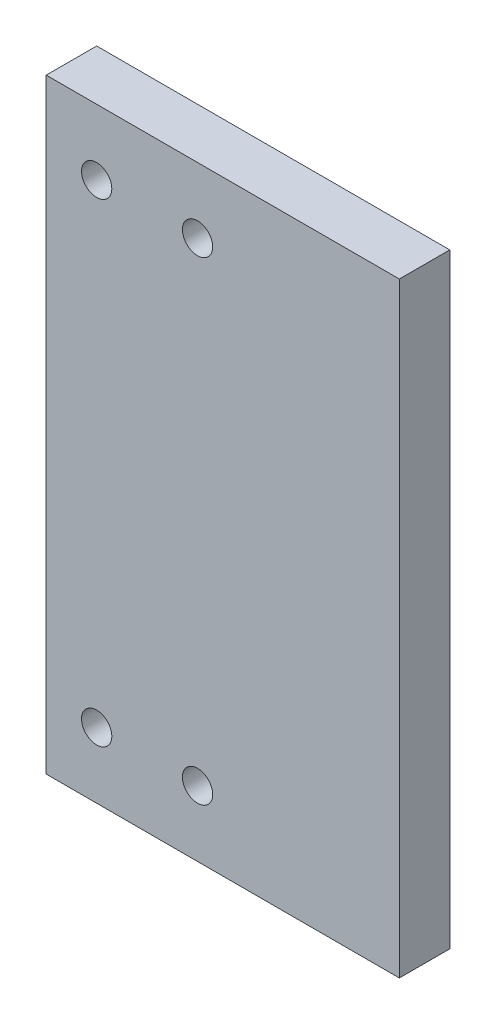
SolidWorks part; units mm, degrees
ref_plane "Plan de face" through (0, 0, 0) normal (0, 0, 1) x (1, 0, 0)
ref_plane "Plan de dessus" through (0, 0, 0) normal (0, 1, 0) x (1, 0, 0)
ref_plane "Plan de droite" through (0, 0, 0) normal (1, 0, 0) x (0, 0, -1)
sketch "Esquisse1" plane through (0, 0, 0) normal (0, 0, 1) x (1, 0, 0)
  line L0 (10, 50) -> (10, 10) construction
  line L1 (0, 0) -> (35, 0)
  line L2 (0, 0) -> (0, 10)
  line L3 (0, 60) -> (35, 60)
  line L4 (35, 0) -> (35, 60)
  line L5 (0, 10) -> (20, 10) construction
  line L6 (0, 50) -> (0, 10)
  line L7 (0, 50) -> (20, 50) construction
  line L8 (20, 10) -> (20, 50) construction
  line L9 (0, 30) -> (20, 30) construction
  line L10 (0, 50) -> (0, 60)
  circle A0 centre (5, 53.5) radius 1.5
  circle A1 centre (15, 53.5) radius 1.5
  circle A2 centre (15, 6.5) radius 1.5
  circle A3 centre (5, 6.5) radius 1.5
  dimension "D3" = 3.5
  dimension "D8" = 3
  dimension "D1" = 20
  dimension "D2" = 40
  dimension "D4" = 5
  dimension "D5" = 60
  dimension "D6" = 10
  dimension "D7" = 35
extrude "Boss.-Extru.1" add sketch "Esquisse1" along normal blind 5
